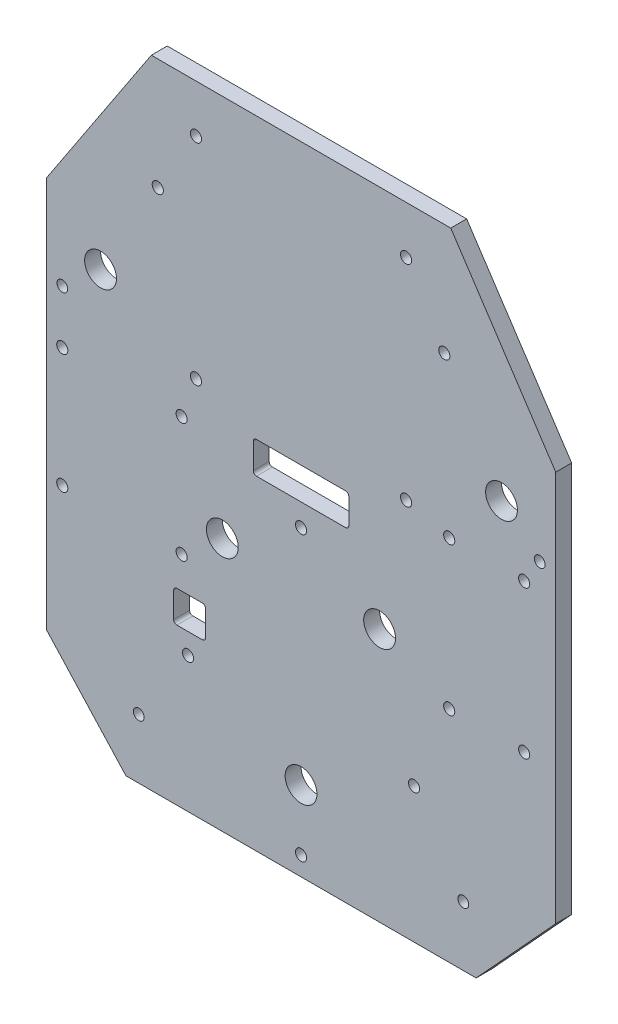
SolidWorks part; units mm, degrees
ref_plane "Plan de face" through (0, 0, 0) normal (1, 0, 0) x (0, 1, 0)
ref_plane "Plan de dessus" through (0, 0, 0) normal (0, 0, 1) x (0, 1, 0)
ref_plane "Plan de droite" through (0, 0, 0) normal (0, 1, 0) x (-1, 0, 0)
sketch "Esquisse1" plane through (0, 0, 0) normal (0, 0, 1) x (0, 1, 0)
  line L0 (0, 0) -> (-150.5414, 0) construction
  line L1 (-100, -80) -> (100, -80)
  line L2 (-100, -80) -> (-100, 80)
  line L3 (-100, 80) -> (100, 80)
  line L5 (-100, -80) -> (100, 80) construction
  line L6 (-100, 80) -> (100, -80) construction
  line L12 (-31, 38.8179) -> (-31, 42.3315) construction
  line L13 (-51, 40) -> (-41, 40)
  line L17 (-51, 40) -> (-51, 30)
  line L18 (-51, 30) -> (-41, 30)
  line L19 (-41, 40) -> (-41, 30)
  line L21 (-31.059, 37.5) -> (-30.571, 37.5) construction
  line L22 (-31, -46.5413) -> (-34.2714, -46.5413) construction
  line L28 (100, 80) -> (100, -80)
  line L30 (2, 15) -> (12, 15)
  line L31 (2, 15) -> (2, -15)
  line L32 (2, -15) -> (12, -15)
  line L33 (12, 15) -> (12, -15)
  circle A0 centre (-75, 0) radius 5
  circle A1 centre (-57.5, 35.5) radius 1.75
  circle A2 centre (-57.5, -35.5) radius 1.75
  circle A3 centre (65, 45) radius 1.75
  circle A4 centre (65, -45) radius 1.75
  circle A5 centre (-31, 37.5) radius 1.75
  circle A6 centre (-31, 75) radius 1.75
  circle A7 centre (6.5, 75) radius 1.75
  circle A8 centre (6.5, 37.5) radius 1.75
  circle A9 centre (-31, -46.5413) radius 1.75
  circle A10 centre (-31, -70.0913) radius 1.75
  circle A11 centre (15.5, -46.5413) radius 1.75
  circle A12 centre (15.5, -70.0913) radius 1.75
  circle A13 centre (-4.9993, 0) radius 1.75
  circle A16 centre (85, 33) radius 1.75
  circle A17 centre (85.0012, -33) radius 1.75
  circle A18 centre (19, 33) radius 1.75
  circle A19 centre (19.0012, -33) radius 1.75
  point P0 (0, 0)
  dimension "D3" = 10
  dimension "D9" = 3.5
  dimension "D10" = 35.5
  dimension "D11" = 17.5
  dimension "D5" = 3.5
  dimension "D6" = 45
  dimension "D7" = 15
  dimension "D16" = 37.5
  dimension "D17" = 37.5
  dimension "D18" = 37.5
  dimension "D19" = 3.5
  dimension "D20" = 3.5
  dimension "D21" = 3.5
  dimension "D22" = 3.5
  dimension "D23" = 10
  dimension "D24" = 5
  dimension "D25" = 3.5
  dimension "D26" = 3.5
  dimension "D27" = 3.5
  dimension "D28" = 3.5
  dimension "D29" = 46.5
  dimension "D30" = 46.5
  dimension "D31" = 23.55
  dimension "D32" = 23.55
  dimension "D35" = 3.5
  dimension "D36" = 3.5
  dimension "D41" = 66
  dimension "D42" = 66
  dimension "D47" = 3.5
  dimension "D48" = 3.5
  dimension "D50" = 66
  dimension "D52" = 33
  dimension "D33" = 14.9988
  dimension "D34" = 3.5
  dimension "D40" = 66
  dimension "D1" = 200
  dimension "D2" = 160
  dimension "D4" = 25
  dimension "D8" = 6.5
  dimension "D12" = 10
  dimension "D13" = 10
  dimension "D14" = 40
  dimension "D15" = 37.5
  dimension "D37" = 15
  dimension "D38" = 15
  dimension "D39" = 10
  dimension "D43" = 102
extrude "Boss.-Extru.1" add sketch "Esquisse1" along normal blind 5
fillet "Congé2" radius 1 8 edges at (-30, -51, 2.5) (-30, -41, 2.5) (-40, -41, 2.5) (-40, -51, 2.5) (15, 2, 2.5) (15, 12, 2.5) (-15, 12, 2.5) (-15, 2, 2.5)
sketch "Esquisse2" plane through (0, 0, 5) normal (0, 0, 1) x (1, 0, 0)
  line L0 (-110, 40) -> (0, 160)
  line L1 (0, 160) -> (110, 40)
  line L2 (110, 40) -> (110, -40)
  line L3 (110, -40) -> (0, -160)
  line L5 (0, -160) -> (-110, -40)
  line L6 (-110, -40) -> (-110, 40)
  line L14 (-573.5804, 598.1671) -> (-698.6982, -488.0825)
  line L15 (-80, 100) -> (-80, -100) construction
  line L16 (80, -100) -> (80, 100) construction
  line L17 (0, 70) -> (0, 33.5097) construction
  line L18 (-698.6982, -488.0825) -> (684.3, -647.3807)
  line L19 (0, 0) -> (-114.7759, 0) construction
  line L20 (684.3, -647.3807) -> (762.9047, 702.4319)
  line L21 (762.9047, 702.4319) -> (-573.5804, 598.1671)
  dimension "D1" = 160
  dimension "D2" = 160
  dimension "D3" = 40
  dimension "D4" = 40
  dimension "D5" = 40
  dimension "D6" = 40
  dimension "D7" = 110
extrude "Enlèv. mat.-Extru.1" cut sketch "Esquisse2" against normal through all
sketch "Esquisse3" plane through (0, 0, 0) normal (0, 0, 1) x (0, 1, 0)
  circle A0 centre (-94.0015, 0.004) radius 1.75
extrude "Trou cuve direction" cut sketch "Esquisse3" along normal through all
sketch "Esquisse4" plane through (0, 0, 5) normal (0, 0, 1) x (1, 0, 0)
  line L0 (-82.024, 47.0385) -> (-45.024, 103.0385)
  line L1 (-45.024, 103.0385) -> (-83.024, 103.0385)
  line L2 (-83.024, 103.0385) -> (-83.024, 47.0385)
  line L3 (-83.024, 47.0385) -> (-82.024, 47.0385)
  line L4 (82.016, 47.0385) -> (45.016, 103.0385)
  line L5 (45.016, 103.0385) -> (83.016, 103.0385)
  line L6 (83.016, 103.0385) -> (83.016, 47.0385)
  line L7 (83.016, 47.0385) -> (82.016, 47.0385)
  circle A0 centre (-50.974, -81.2615) radius 1.7
  circle A1 centre (-74.974, 23.2385) radius 1.7
  circle A2 centre (50.966, -81.2615) radius 1.7
  circle A3 centre (74.966, 23.2385) radius 1.7
  circle A4 centre (-62.974, 33.7385) radius 5
  circle A5 centre (62.966, 33.7385) radius 5
  circle A6 centre (-24.724, -20.2615) radius 5
  circle A7 centre (24.676, -20.2615) radius 5
extrude "Pointe avant, trous batteries et cables" cut sketch "Esquisse4" against normal through all
